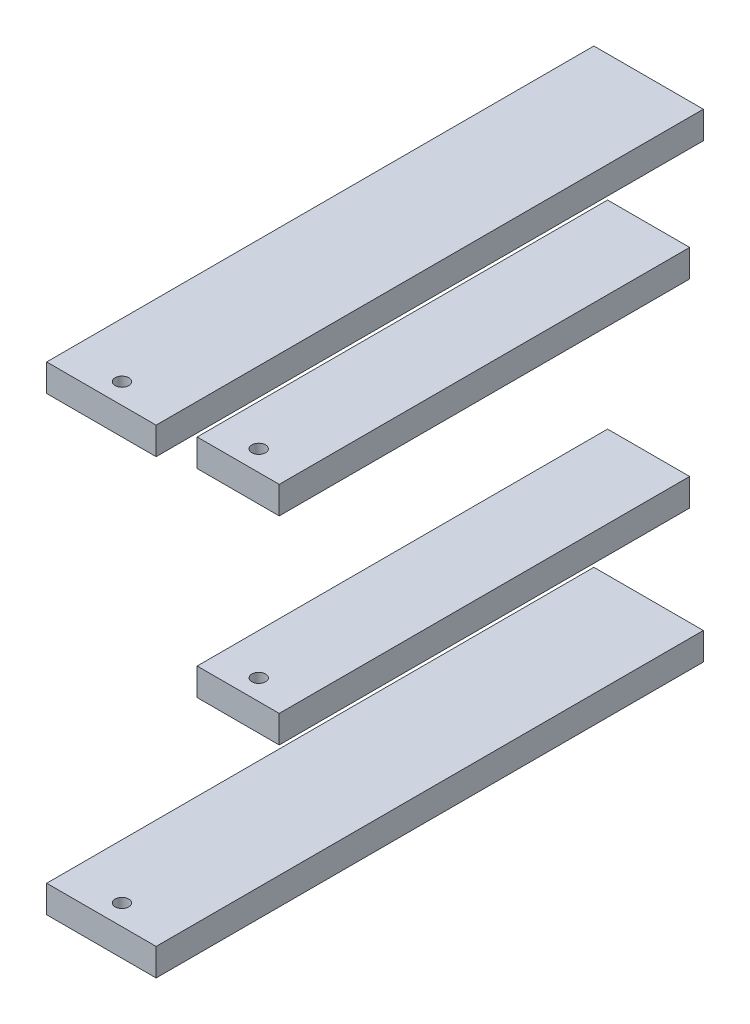
SolidWorks part; units mm, degrees
ref_plane "Спереди" through (0, 0, 0) normal (0, 0, 1) x (1, 0, 0)
ref_plane "Сверху" through (0, 0, 0) normal (0, 1, 0) x (1, 0, 0)
ref_plane "Справа" through (0, 0, 0) normal (1, 0, 0) x (0, 0, -1)
sketch "Эскиз1" plane through (0, 0, 0) normal (0, 0, 1) x (1, 0, 0)
  line L0 (-299.134, 0) -> (299.134, 0) construction
  line L1 (-299.134, 155) -> (299.134, 155) construction
  line L2 (-299.134, -155) -> (299.134, -155) construction
  line L3 (556.486, 62.5) -> (-950.8619, 62.5) construction
  line L4 (556.486, -62.5) -> (-950.8619, -62.5) construction
  line L5 (0, 155) -> (0, -155) construction
  line L6 (-40, 155) -> (40, 155)
  line L7 (-40, 155) -> (-40, 175)
  line L8 (-40, 175) -> (40, 175)
  line L9 (40, 155) -> (40, 175)
  line L10 (-40, -175) -> (40, -175)
  line L11 (-40, -175) -> (-40, -155)
  line L12 (-40, -155) -> (40, -155)
  line L13 (40, -175) -> (40, -155)
  point P3 (0, 155)
  point P4 (0, 0)
  point P8 (0, 155)
  point P23 (0, -155)
  point P26 (0, -155)
  dimension "D1" = 155
  dimension "D2" = 62.5
  dimension "D3" = 20
  dimension "D4" = 80
  dimension "D5" = 80
  dimension "D6" = 20
extrude "Бобышка-Вытянуть1" add sketch "Эскиз1" along normal blind 400
sketch "Эскиз3" plane through (0, -175, 0) normal (0, -1, 0) x (1, 0, 0)
  line L0 (0, 400) -> (0, 0) construction
  line L1 (-40, 400) -> (40, 400) construction
  circle A0 centre (0, 385) radius 5
  dimension "D1" = 10
  dimension "D2" = 15
extrude "Вырез-Вытянуть1" cut sketch "Эскиз3" against normal blind 400
sketch "Эскиз4" plane through (0, 0, 0) normal (0, 0, 1) x (1, 0, 0)
  line L0 (-317.4048, 0) -> (317.4048, 0) construction
  line L1 (125.6238, 62.5) -> (-288.6482, 62.5) construction
  line L2 (110.1988, -62.5) -> (-276.5285, -62.5) construction
  line L3 (0, 155) -> (0, -155) construction
  line L4 (-40, 155) -> (40, 155) construction
  line L5 (40, -155) -> (-40, -155) construction
  line L6 (0, 62.5) -> (0, -62.5) construction
  line L7 (-30, -62.5) -> (-30, -82.5)
  line L8 (-30, 62.5) -> (30, 62.5)
  line L9 (-30, 62.5) -> (-30, 82.5)
  line L10 (-30, 82.5) -> (30, 82.5)
  line L11 (30, 62.5) -> (30, 82.5)
  line L12 (-30, -82.5) -> (30, -82.5)
  line L13 (30, -62.5) -> (30, -82.5)
  line L14 (-30, -62.5) -> (30, -62.5)
  point P4 (0, 0)
  point P16 (0, 0)
  point P18 (0, 62.5)
  dimension "D1" = 62.5
  dimension "D2" = 62.5
  dimension "D3" = 0
  dimension "D4" = 60
  dimension "D5" = 20
extrude "Бобышка-Вытянуть2" add sketch "Эскиз4" along normal blind 300 separate body
sketch "Эскиз5" plane through (0, -82.5, 0) normal (0, -1, 0) x (1, 0, 0)
  line L0 (0, 300) -> (0, 0) construction
  line L1 (-30, 300) -> (30, 300) construction
  line L2 (-30, 0) -> (30, 0) construction
  circle A0 centre (0, 285) radius 5
  dimension "D1" = 10
  dimension "D2" = 15
extrude "Вырез-Вытянуть2" cut sketch "Эскиз5" against normal blind 300
